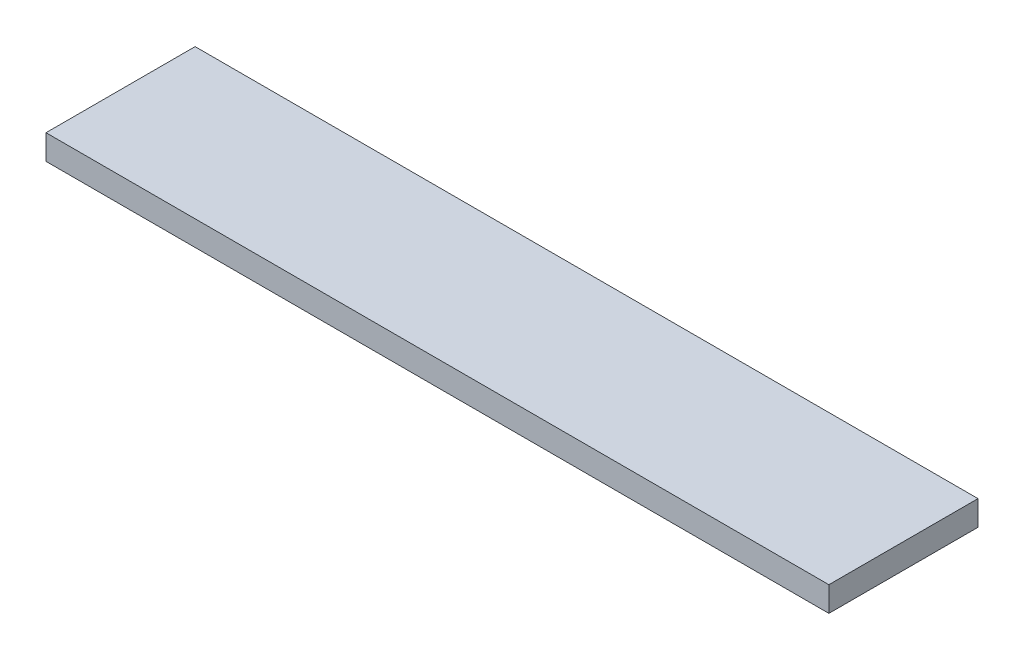
SolidWorks part; units mm, degrees
ref_plane "Front Plane" through (0, 0, 0) normal (0, 0, 1) x (1, 0, 0)
ref_plane "Top Plane" through (0, 0, 0) normal (0, 1, 0) x (1, 0, 0)
ref_plane "Right Plane" through (0, 0, 0) normal (1, 0, 0) x (0, 0, -1)
sketch "Sketch1" plane through (0, 0, 0) normal (0, 1, 0) x (1, 0, 0)
  line L5 (31.5, -6) -> (-31.5, -6)
  line L6 (31.5, -6) -> (31.5, 6)
  line L7 (31.5, 6) -> (-31.5, 6)
  line L8 (-31.5, -6) -> (-31.5, 6)
  line L9 (31.5, -6) -> (-31.5, 6) construction
  line L10 (31.5, 6) -> (-31.5, -6) construction
  point P0 (0, 0)
  dimension "D1" = 63
  dimension "D2" = 12
extrude "Boss-Extrude1" add sketch "Sketch1" along normal blind 2
